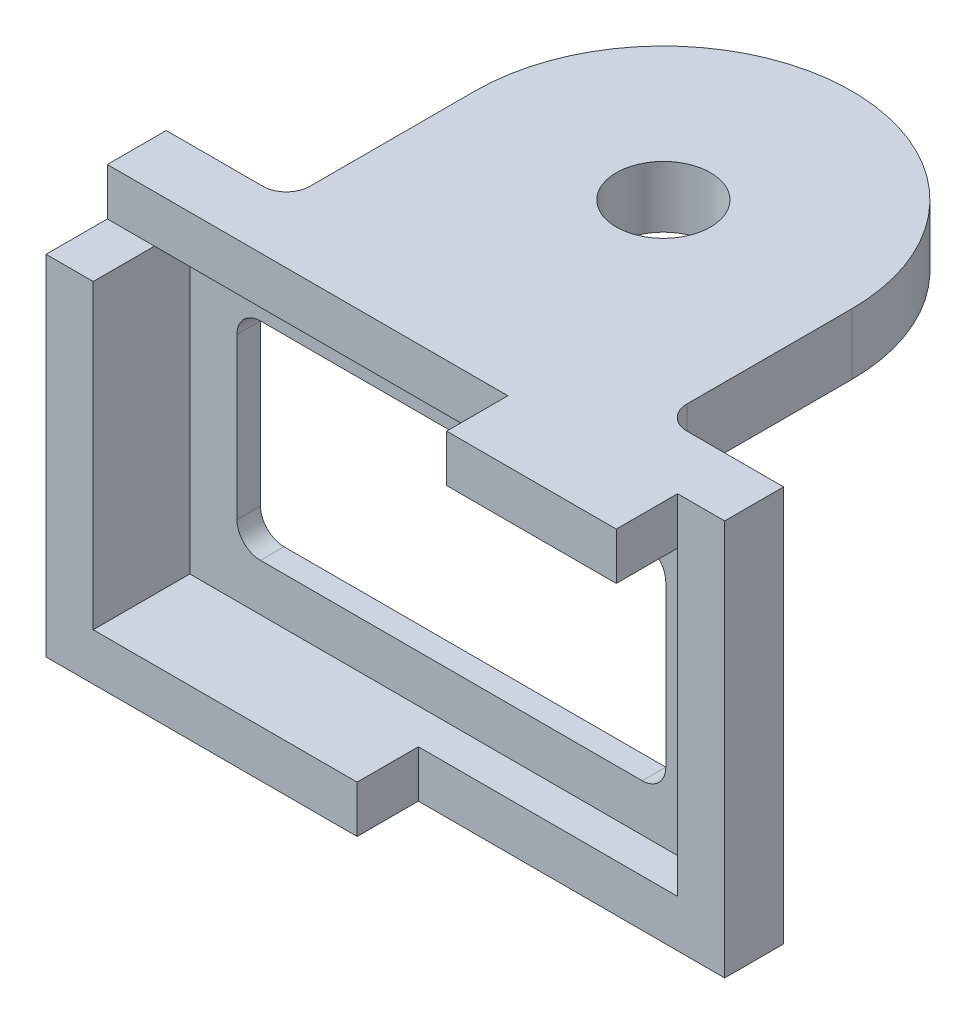
SolidWorks part; units mm, degrees
ref_plane "Front Plane" through (0, 0, 0) normal (0, 0, 1) x (1, 0, 0)
ref_plane "Top Plane" through (0, 0, 0) normal (0, 1, 0) x (1, 0, 0)
ref_plane "Right Plane" through (0, 0, 0) normal (1, 0, 0) x (0, 0, -1)
sketch "Sketch1" plane through (0, 0, 0) normal (0, 0, 1) x (1, 0, 0)
  line L0 (-20.7047, 14.3119) -> (12.5693, 14.3119)
  line L1 (-18.1647, 11.7719) -> (10.0293, 11.7719)
  line L2 (-18.1647, 11.7719) -> (-18.1647, -4.4841)
  line L3 (-18.1647, -4.4841) -> (10.0293, -4.4841)
  line L4 (10.0293, 11.7719) -> (10.0293, -4.4841)
  line L5 (-18.1647, 11.7719) -> (10.0293, 11.7719) construction
  line L6 (-18.1647, 11.7719) -> (-18.1647, 14.8199)
  line L7 (-18.1647, 14.8199) -> (10.0293, 14.8199)
  line L8 (10.0293, 11.7719) -> (10.0293, 14.8199)
  line L9 (12.5693, 14.3119) -> (12.5693, -7.0241)
  line L10 (-20.7047, -7.0241) -> (12.5693, -7.0241)
  line L11 (-20.7047, 14.3119) -> (-20.7047, -7.0241)
  circle A0 centre (6.9813, 8.7239) radius 1.778 construction
  circle A1 centre (-15.1167, -1.4361) radius 1.778 construction
  dimension "D4" = 3.556
  dimension "D5" = 3.556
  dimension "D6" = 3.048
  dimension "D1" = 3.048
  dimension "D2" = 16.256
  dimension "D3" = 28.194
  dimension "D7" = 19.304
  dimension "D8" = 3.048
  dimension "D9" = 3.048
  dimension "D10" = 2.54
extrude "Boss-Extrude1" add sketch "Sketch1" along normal blind 6.477 contours L1 L8 L0 L6 | L0 L11 L10 L9 L8 L4 L3 L2 L6
sketch "Sketch2" plane through (0, 0, 0) normal (0, 0, -1) x (-1, 0, 0)
  line L0 (18.1647, 11.7719) -> (18.1647, -4.4841) construction
  line L1 (18.1647, -4.4841) -> (-10.0293, -4.4841) construction
  line L2 (-10.0293, -4.4841) -> (-10.0293, 11.7719) construction
  line L3 (18.1647, 11.7719) -> (-10.0293, 11.7719) construction
  line L4 (18.1647, 11.7719) -> (18.1647, -4.4841)
  line L5 (18.1647, -4.4841) -> (-10.0293, -4.4841)
  line L6 (-10.0293, -4.4841) -> (-10.0293, 11.7719)
  line L7 (18.1647, 11.7719) -> (-10.0293, 11.7719)
  line L8 (15.6247, 9.2319) -> (15.6247, -1.9441)
  line L9 (15.6247, -1.9441) -> (-7.4893, -1.9441)
  line L10 (-7.4893, -1.9441) -> (-7.4893, 9.2319)
  line L11 (15.6247, 9.2319) -> (-7.4893, 9.2319)
  dimension "D1" = 2.54
extrude "Boss-Extrude2" add sketch "Sketch2" against normal blind 1.27
sketch "Sketch3" plane through (0, 0, 6.477) normal (0, 0, 1) x (1, 0, 0)
  line L0 (-18.1647, 11.7719) -> (10.0293, 11.7719) construction
  line L1 (-20.7047, 14.3119) -> (0.8853, 14.3119)
  line L2 (-20.7047, 14.3119) -> (-20.7047, 11.7719)
  line L3 (-20.7047, 11.7719) -> (0.8853, 11.7719)
  line L4 (0.8853, 14.3119) -> (0.8853, 11.7719)
  line L5 (-20.7047, -7.0241) -> (12.5693, -7.0241) construction
  line L6 (12.5693, 14.3119) -> (10.0293, 14.3119)
  line L7 (12.5693, 14.3119) -> (12.5693, -7.0241)
  line L8 (12.5693, -7.0241) -> (10.0293, -7.0241)
  line L9 (10.0293, 14.3119) -> (10.0293, -7.0241)
  line L10 (10.0293, -4.4841) -> (10.0293, 11.7719) construction
  line L11 (-18.1647, -4.4841) -> (10.0293, -4.4841) construction
  line L12 (12.5693, -7.0241) -> (-3.9407, -7.0241)
  line L13 (12.5693, -7.0241) -> (12.5693, -4.4841)
  line L14 (12.5693, -4.4841) -> (-3.9407, -4.4841)
  line L15 (-3.9407, -7.0241) -> (-3.9407, -4.4841)
  line M2 (12.5693, 14.3119) -> (-20.7047, 14.3119)
  line M3 (-20.7047, 14.3119) -> (-20.7047, -7.0241)
  line M4 (-20.7047, -7.0241) -> (12.5693, -7.0241)
  line M5 (-18.1647, 11.7719) -> (10.0293, 11.7719)
  line M6 (10.0293, 11.7719) -> (10.0293, -4.4841)
  line M7 (10.0293, -4.4841) -> (-18.1647, -4.4841)
  dimension "D1" = 21.59
  dimension "D2" = 16.51
extrude "Cut-Extrude1" cut sketch "Sketch3" against normal blind 3.302 contours L4 L3 M2 M3 M5 | L14 L7 L9 M2 M6 | L15 L9 M4 M7
sketch "Sketch4" plane through (0, 14.3119, 0) normal (0, 1, 0) x (1, 0, 0)
  line L0 (-20.7047, 0) -> (12.5693, 0) construction
  line L1 (-4.0677, 0) -> (-4.0677, 30.9829) construction
  line L2 (-14.2277, 10.16) -> (-14.2277, 0)
  line L3 (6.0923, 10.16) -> (6.0923, 0)
  line L4 (-14.2277, 0) -> (6.0923, 0)
  arc A0 (6.0923, 10.16) -> (-14.2277, 10.16) centre (-4.0677, 10.16) ccw
  circle A1 centre (-4.0677, 10.16) radius 2.54
  dimension "D1" = 5.08
  dimension "D2" = 10.16
extrude "Boss-Extrude3" add sketch "Sketch4" against normal blind 3.302
fillet "Fillet4" radius 1.27 7 edges at (-15.6247, 9.2319, 0.635) (-15.6247, -1.9441, 0.635) (7.4893, -1.9441, 0.635) (7.4893, 9.2319, 0.635) (-14.2277, 12.6609, 0) (6.0923, 12.6609, 0) (-4.0677, 11.0099, 0)
